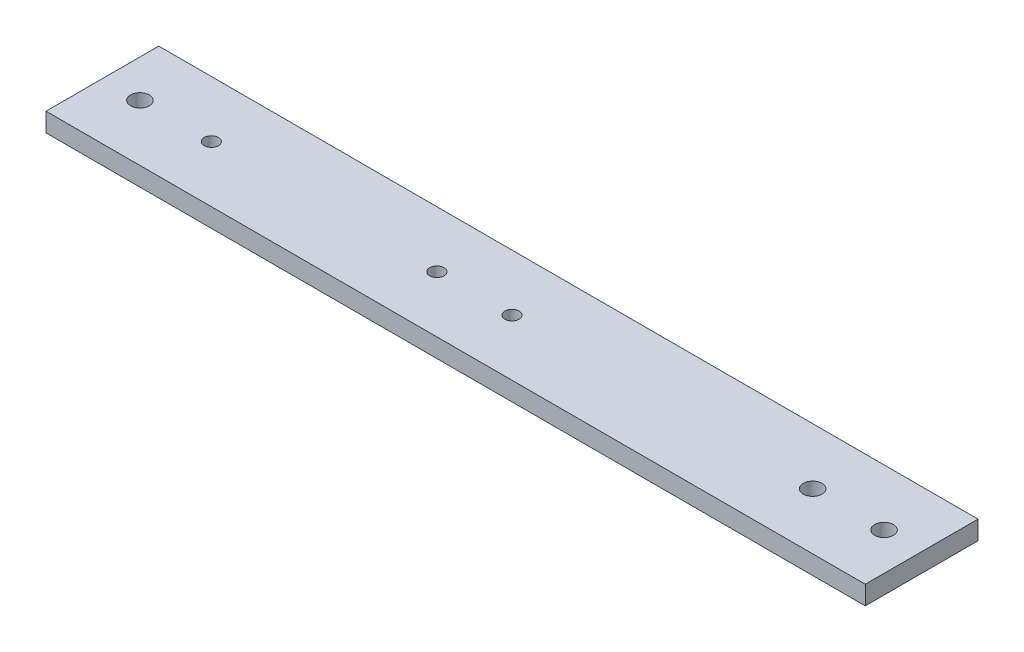
SolidWorks part; units mm, degrees
ref_plane "Front Plane" through (0, 0, 0) normal (0, 0, 1) x (1, 0, 0)
ref_plane "Top Plane" through (0, 0, 0) normal (0, 1, 0) x (1, 0, 0)
ref_plane "Right Plane" through (0, 0, 0) normal (1, 0, 0) x (0, 0, -1)
sketch "Sketch1" plane through (0, 0, 0) normal (0, 1, 0) x (1, 0, 0)
  line L0 (-138.43, 0) -> (138.43, 0) construction
  line L1 (-138.43, -19.05) -> (138.43, -19.05)
  line L2 (-138.43, -19.05) -> (-138.43, 19.05)
  line L3 (-138.43, 19.05) -> (138.43, 19.05)
  line L4 (138.43, -19.05) -> (138.43, 19.05)
  line L5 (-138.43, -19.05) -> (138.43, 19.05) construction
  line L6 (-138.43, 19.05) -> (138.43, -19.05) construction
  line L7 (-101.6, 0) -> (-138.43, 0) construction
  line L8 (101.6, 0) -> (138.43, 0) construction
  circle A0 centre (-125.73, 0) radius 3.175
  circle A1 centre (125.73, 0) radius 3.175
  circle A2 centre (-101.6, 0) radius 2.413
  circle A3 centre (-25.4, 0) radius 2.413
  circle A4 centre (0, 0) radius 2.413
  circle A5 centre (101.6, 0) radius 3.175
  point P0 (0, 0)
  dimension "D3" = 6.35
  dimension "D4" = 12.7
  dimension "D5" = 12.7
  dimension "D6" = 76.2
  dimension "D7" = 4.826
  dimension "D8" = 4.826
  dimension "D9" = 6.35
  dimension "D10" = 101.6
  dimension "D13" = 25.4
  dimension "D1" = 38.1
  dimension "D2" = 276.86
extrude "Boss-Extrude1" add sketch "Sketch1" along normal blind 6.35
